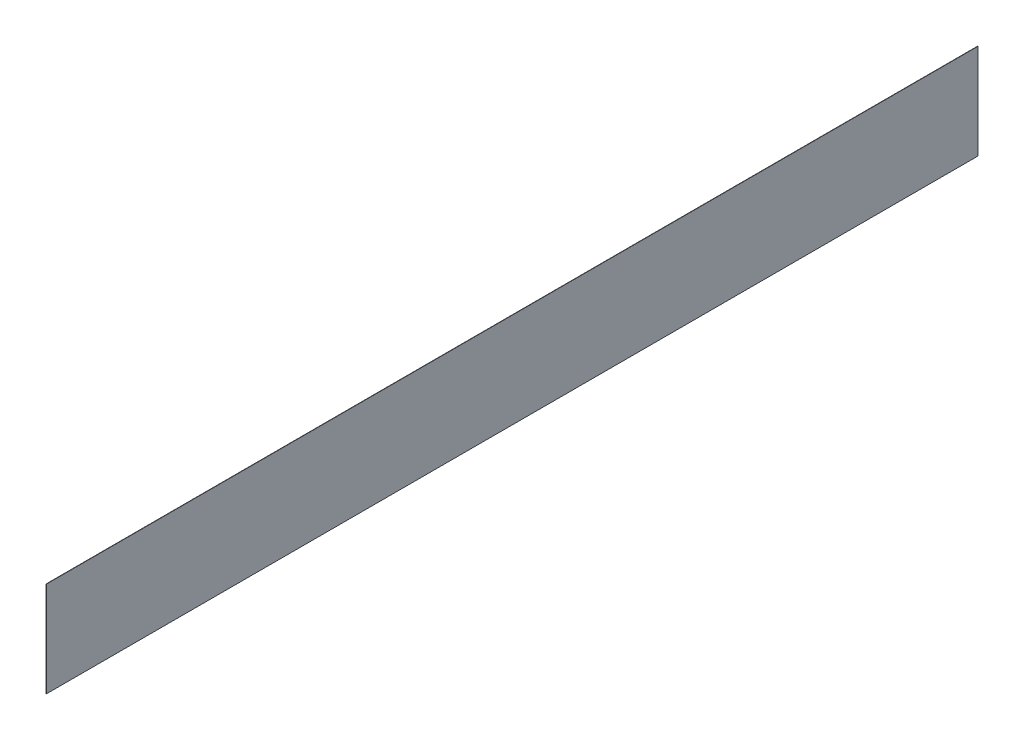
SolidWorks part; units mm, degrees
ref_plane "Ön Düzlem" through (0, 0, 0) normal (0, 0, 1) x (1, 0, 0)
ref_plane "Üst Düzlem" through (0, 0, 0) normal (0, 1, 0) x (1, 0, 0)
ref_plane "Sağ Düzlem" through (0, 0, 0) normal (1, 0, 0) x (0, 0, -1)
sketch "Sketch1" plane through (0, 0, 0) normal (1, 0, 0) x (0, 0, -1)
  line L0 (0, -15) -> (2940, -15) construction
  line L1 (0, 0) -> (550, 0)
  line L2 (0, 0) -> (0, -300)
  line L3 (0, -300) -> (550, -300)
  line L4 (550, 0) -> (550, -300)
  line L5 (550, 0) -> (650, 0)
  line L6 (550, 0) -> (550, -300)
  line L7 (550, -300) -> (650, -300)
  line L8 (650, 0) -> (650, -300)
  line L9 (650, 0) -> (1370, 0)
  line L10 (650, 0) -> (650, -300)
  line L11 (650, -300) -> (1370, -300)
  line L12 (1370, 0) -> (1370, -300)
  line L13 (1370, 0) -> (1470, 0)
  line L14 (1370, 0) -> (1370, -300)
  line L15 (1370, -300) -> (1470, -300)
  line L16 (1470, 0) -> (1470, -300)
  line L17 (1470, 0) -> (2020, 0)
  line L18 (1470, 0) -> (1470, -300)
  line L19 (1470, -300) -> (2020, -300)
  line L20 (2020, 0) -> (2020, -300)
  line L21 (2020, 0) -> (2120, 0)
  line L22 (2020, 0) -> (2020, -300)
  line L23 (2020, -300) -> (2120, -300)
  line L24 (2120, 0) -> (2120, -300)
  line L25 (2120, 0) -> (2840, 0)
  line L26 (2120, 0) -> (2120, -300)
  line L27 (2120, -300) -> (2840, -300)
  line L28 (2840, 0) -> (2840, -300)
  line L29 (2840, 0) -> (2940, 0)
  line L30 (2840, 0) -> (2840, -300)
  line L31 (2840, -300) -> (2940, -300)
  line L32 (2940, 0) -> (2940, -300)
  line L33 (0, -30) -> (2940, -30) construction
  dimension "D1" = 550
  dimension "D2" = 300
  dimension "D3" = 100
  dimension "D4" = 100
  dimension "D5" = 100
  dimension "D6" = 720
  dimension "D7" = 550
  dimension "D8" = 720
  dimension "D9" = 100
  dimension "D10" = 15
  dimension "D11" = 15
extrude "Boss-Extrude1" add sketch "Sketch1" against normal blind 1 contours L4 L1 L2 L3 | L12 L9 L8 L11 | L8 L5 L4 L7 | L16 L13 L12 L15 | L20 L17 L16 L19 | L24 L21 L20 L23 | L28 L25 L24 L27 | L32 L29 L28 L31
